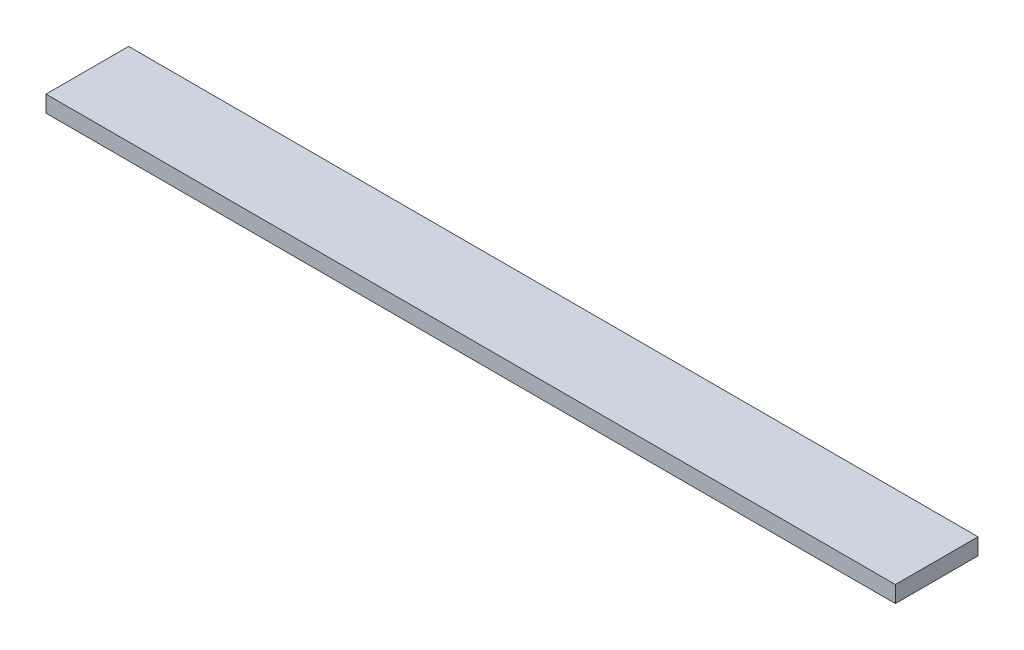
SolidWorks part; units mm, degrees
material "SBR"
ref_plane "前视基准面" through (0, 0, 0) normal (0, 0, 1) x (1, 0, 0)
ref_plane "上视基准面" through (0, 0, 0) normal (0, 1, 0) x (1, 0, 0)
ref_plane "右视基准面" through (0, 0, 0) normal (1, 0, 0) x (0, 0, -1)
sketch "草图1" plane through (0, 0, 0) normal (0, 1, 0) x (1, 0, 0)
  line L1 (128.5, -12.5) -> (-128.5, -12.5)
  line L2 (128.5, -12.5) -> (128.5, 12.5)
  line L3 (128.5, 12.5) -> (-128.5, 12.5)
  line L4 (-128.5, -12.5) -> (-128.5, 12.5)
  line L5 (128.5, -12.5) -> (-128.5, 12.5) construction
  line L6 (128.5, 12.5) -> (-128.5, -12.5) construction
  point P0 (0, 0)
  dimension "D1" = 257
  dimension "D2" = 25
extrude "凸台-拉伸1" add sketch "草图1" along normal blind 5
